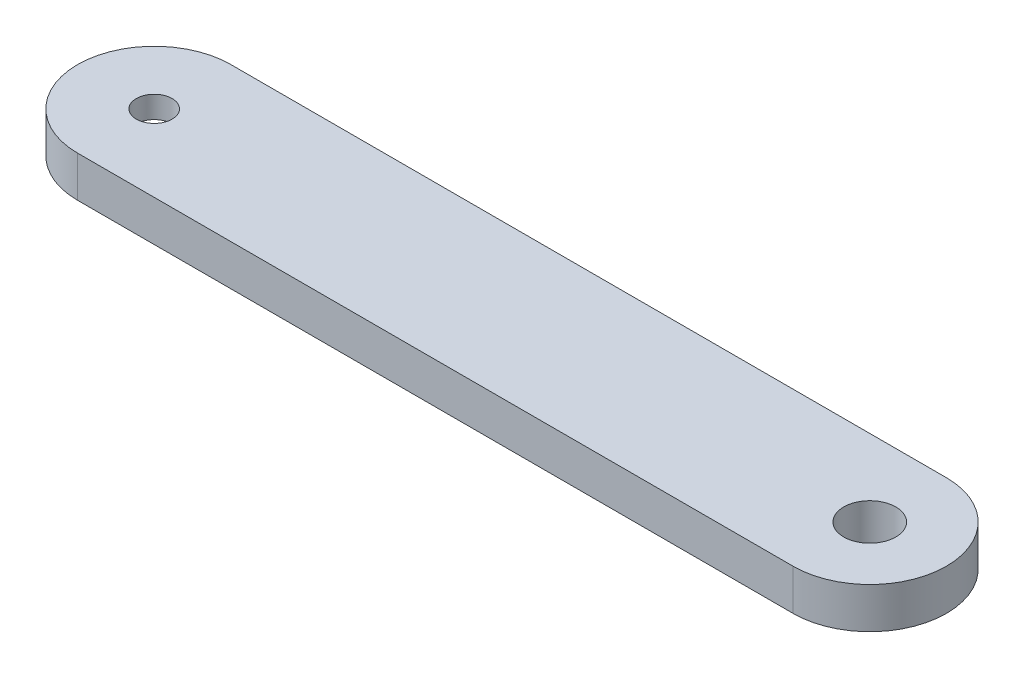
SolidWorks part; units mm, degrees
ref_plane "Piano frontale" through (0, 0, 0) normal (0, 0, 1) x (1, 0, 0)
ref_plane "Piano superiore" through (0, 0, 0) normal (0, 1, 0) x (1, 0, 0)
ref_plane "Piano destro" through (0, 0, 0) normal (1, 0, 0) x (0, 0, -1)
sketch "Schizzo2" plane through (0, 0, 0) normal (0, 1, 0) x (1, 0, 0)
  line L0 (70, 0) -> (-70, 0) construction
  line L1 (70, -15) -> (-70, -15)
  line L2 (70, 15) -> (-70, 15)
  arc A0 (70, -15) -> (70, 15) centre (70, 0) ccw
  arc A1 (-70, 15) -> (-70, -15) centre (-70, 0) ccw
  circle A2 centre (70, 0) radius 5.1
  circle A3 centre (-70, 0) radius 3.5
  point P3 (0, 0)
  dimension "D3" = 10.2
  dimension "D4" = 7
  dimension "D1" = 140
  dimension "D2" = 15
extrude "Estrusione-Estrusione1" add sketch "Schizzo2" along normal blind 8
sketch "Schizzo4" plane through (0, 0, 0) normal (0, -1, 0) x (1, 0, 0)
  circle A0 centre (-70, 0) radius 11
  dimension "D1" = 22
extrude "Taglio-Estrusione1" cut sketch "Schizzo4" against normal blind 3.7
sketch "Schizzo5" plane through (0, 3.7, 0) normal (0, -1, 0) x (1, 0, 0)
  line L0 (-70, 0) -> (-70, 9.9693) construction
  line L1 (-60.4234, 0) -> (-79.7541, 0) construction
  circle A0 centre (-75.66, 5.66) radius 1.1
  circle A1 centre (-64.34, 5.66) radius 1.1
  circle A2 centre (-64.34, -5.66) radius 1.1
  circle A3 centre (-75.66, -5.66) radius 1.1
  dimension "D1" = 2.2
  dimension "D2" = 5.66
  dimension "D3" = 5.66
extrude "Taglio-Estrusione2" cut sketch "Schizzo5" against normal blind 3
